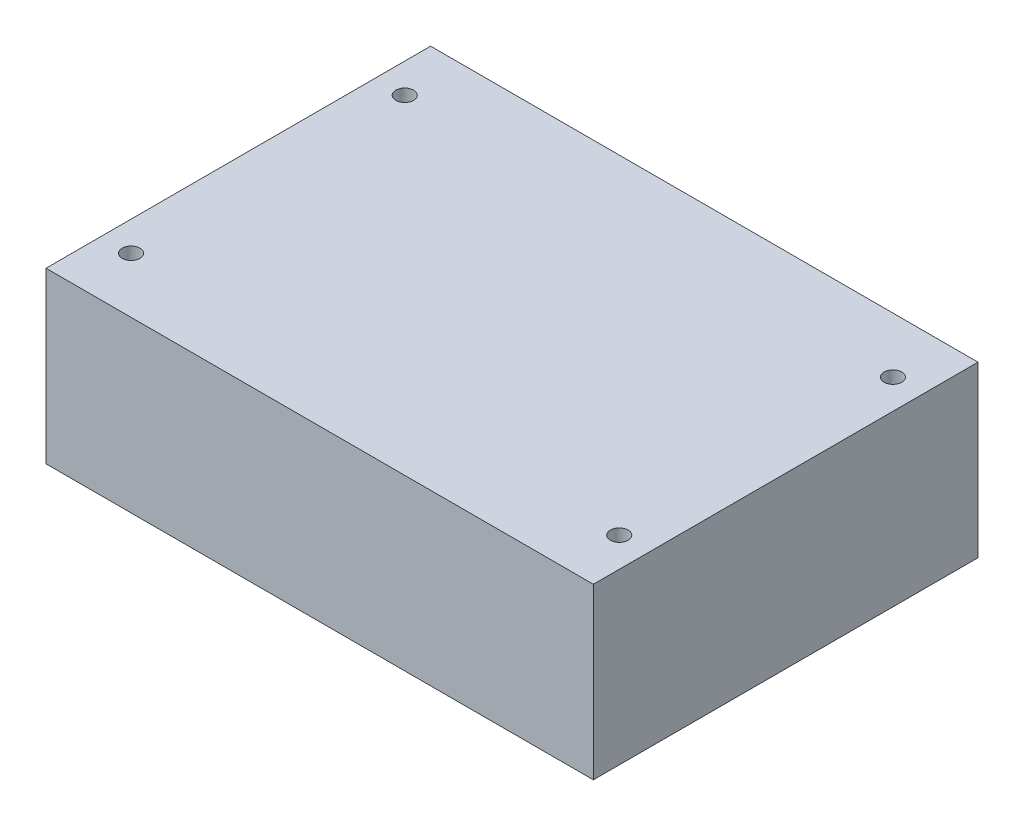
SolidWorks part; units mm, degrees
ref_plane "Alzado" through (0, 0, 0) normal (0, 0, 1) x (1, 0, 0)
ref_plane "Planta" through (0, 0, 0) normal (0, 1, 0) x (1, 0, 0)
ref_plane "Vista lateral" through (0, 0, 0) normal (1, 0, 0) x (0, 0, -1)
sketch "Croquis1" plane through (0, 11, 0) normal (0, 1, 0) x (1, 0, 0)
  line L1 (63.9899, 47.5341) -> (137.9899, 47.5341)
  line L2 (63.9899, 47.5341) -> (63.9899, 99.5341)
  line L3 (63.9899, 99.5341) -> (137.9899, 99.5341)
  line L4 (137.9899, 47.5341) -> (137.9899, 99.5341)
  dimension "D1" = 52
  dimension "D2" = 74
extrude "Saliente-Extruir1" add sketch "Croquis1" along normal blind 22.9 contours L2 L1 L4 L3
sketch "Croquis2" plane through (0, 33.9, 0) normal (0, 1, 0) x (1, 0, 0)
  line L0 (67.9899, 92.0341) -> (133.9899, 92.0341) construction
  line L2 (63.9899, 99.5341) -> (137.9899, 99.5341) construction
  line L3 (67.9899, 92.0341) -> (67.9899, 55.0341) construction
  line L4 (63.9899, 47.5341) -> (63.9899, 99.5341) construction
  circle A0 centre (67.9899, 92.0341) radius 1
  circle A1 centre (67.9899, 55.0341) radius 1
  circle A2 centre (133.9899, 92.0341) radius 1
  circle A3 centre (133.9899, 55.0341) radius 1
  point P8 (100.9899, 99.5341)
  point P11 (100.9899, 92.0341)
  point P15 (63.9899, 73.5341)
  point P16 (67.9899, 73.5341)
  dimension "D3" = 2
  dimension "D1" = 66
  dimension "D2" = 37
hole_wizard "Taladro de margen para M21" positions "Croquis3" profile "Croquis5" hole size "M2" standard "Ansi Metric"
sketch "Croquis3" plane through (0, 33.9, 0) normal (0, 1, 0) x (1, 0, 0)
  point P0 (67.9899, 92.0341)
  point P3 (133.9899, 92.0341)
  point P6 (133.9899, 55.0341)
  point P9 (67.9899, 55.0341)
sketch "Croquis5" plane through (67.9899, 33.9, -92.0341) normal (1, 0, 0) x (0, 0, 1)
  line L0 (0, 0) -> (0, 3.221)
  line L1 (0, 3.221) -> (1.2, 2.5)
  line L2 (1.2, 2.5) -> (1.2, 0)
  line L5 (1.2, 0) -> (0, 0)
  line L10 (0, 3.221) -> (-1.2, 2.5) construction
  line L11 (0, -6.35) -> (0, 107.95) construction
  dimension "Diámetro de taladro" = 2.4
  dimension "Profundidad de taladro" = 2.5
  dimension "Ángulo de perforador" = 118
